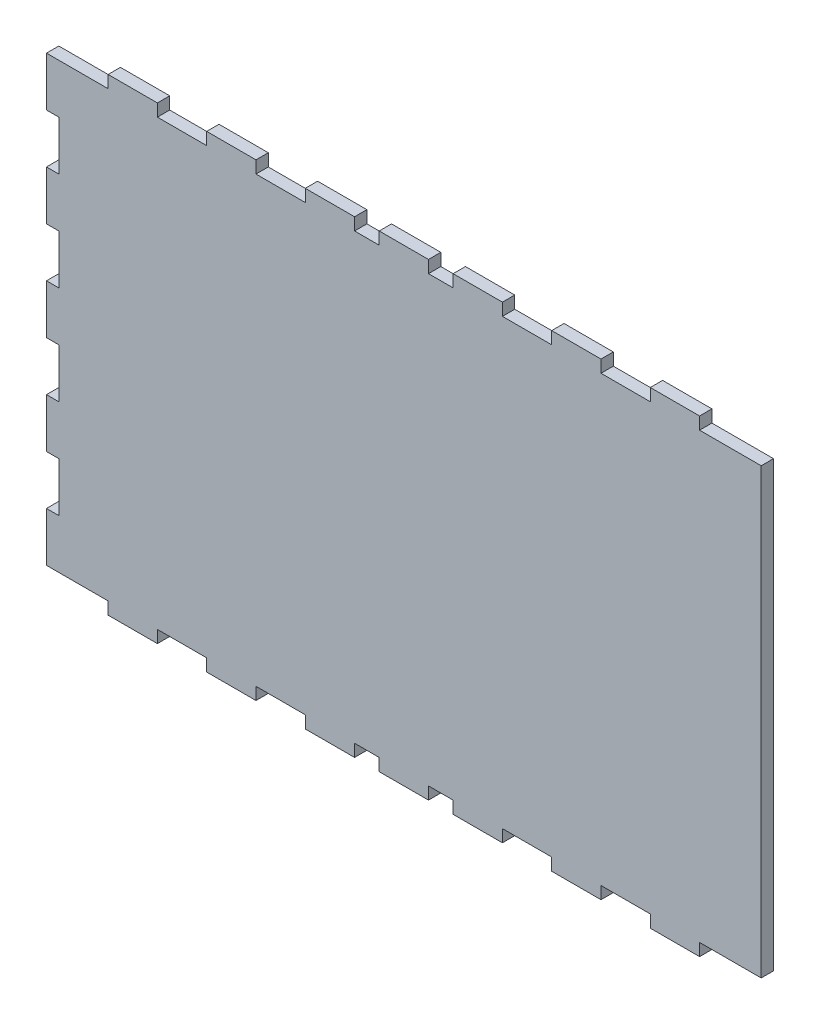
SolidWorks part; units mm, degrees
ref_plane "Front Plane" through (0, 0, 0) normal (0, 0, 1) x (1, 0, 0)
ref_plane "Top Plane" through (0, 0, 0) normal (0, 1, 0) x (1, 0, 0)
ref_plane "Right Plane" through (0, 0, 0) normal (1, 0, 0) x (0, 0, -1)
sketch "Sketch1" plane through (0, 0, 0) normal (0, 0, 1) x (1, 0, 0)
  line L0 (132.5156, 19.2892) -> (164.2656, 19.2892)
  line L1 (164.2656, 19.2892) -> (164.2656, 25.6392)
  line L2 (164.2656, 25.6392) -> (189.6656, 25.6392)
  line L3 (189.6656, 25.6392) -> (189.6656, 19.2892)
  line L4 (189.6656, 19.2892) -> (215.0656, 19.2892)
  line L5 (215.0656, 19.2892) -> (215.0656, 25.6392)
  line L6 (215.0656, 25.6392) -> (240.4656, 25.6392)
  line L7 (240.4656, 25.6392) -> (240.4656, 19.2892)
  line L8 (240.4656, 19.2892) -> (265.8656, 19.2892)
  line L9 (265.8656, 19.2892) -> (265.8656, 25.6392)
  line L10 (265.8656, 25.6392) -> (291.2656, 25.6392)
  line L11 (291.2656, 25.6392) -> (291.2656, 19.2892)
  line L12 (500.8156, 19.2892) -> (469.0656, 19.2892)
  line L13 (469.0656, 19.2892) -> (469.0656, 25.6392)
  line L14 (469.0656, 25.6392) -> (443.6656, 25.6392)
  line L15 (443.6656, 25.6392) -> (443.6656, 19.2892)
  line L16 (443.6656, 19.2892) -> (418.2656, 19.2892)
  line L17 (418.2656, 19.2892) -> (418.2656, 25.6392)
  line L18 (418.2656, 25.6392) -> (392.8656, 25.6392)
  line L19 (392.8656, 25.6392) -> (392.8656, 19.2892)
  line L20 (392.8656, 19.2892) -> (367.4656, 19.2892)
  line L21 (367.4656, 19.2892) -> (367.4656, 25.6392)
  line L22 (367.4656, 25.6392) -> (342.0656, 25.6392)
  line L23 (342.0656, 25.6392) -> (342.0656, 19.2892)
  line L24 (291.2656, 19.2892) -> (303.9656, 19.2892)
  line L25 (303.9656, 19.2892) -> (303.9656, 25.6392)
  line L26 (303.9656, 25.6392) -> (329.3656, 25.6392)
  line L27 (329.3656, 25.6392) -> (329.3656, 19.2892)
  line L28 (329.3656, 19.2892) -> (342.0656, 19.2892)
  line L29 (132.5156, -209.3108) -> (164.2656, -209.3108)
  line L30 (164.2656, -209.3108) -> (164.2656, -215.6608)
  line L31 (164.2656, -215.6608) -> (189.6656, -215.6608)
  line L32 (189.6656, -215.6608) -> (189.6656, -209.3108)
  line L33 (189.6656, -209.3108) -> (215.0656, -209.3108)
  line L34 (215.0656, -209.3108) -> (215.0656, -215.6608)
  line L35 (215.0656, -215.6608) -> (240.4656, -215.6608)
  line L36 (240.4656, -215.6608) -> (240.4656, -209.3108)
  line L37 (240.4656, -209.3108) -> (265.8656, -209.3108)
  line L38 (265.8656, -209.3108) -> (265.8656, -215.6608)
  line L39 (265.8656, -215.6608) -> (291.2656, -215.6608)
  line L40 (291.2656, -215.6608) -> (291.2656, -209.3108)
  line L41 (500.8156, -209.3108) -> (469.0656, -209.3108)
  line L42 (469.0656, -209.3108) -> (469.0656, -215.6608)
  line L43 (469.0656, -215.6608) -> (443.6656, -215.6608)
  line L44 (443.6656, -215.6608) -> (443.6656, -209.3108)
  line L45 (443.6656, -209.3108) -> (418.2656, -209.3108)
  line L46 (418.2656, -209.3108) -> (418.2656, -215.6608)
  line L47 (418.2656, -215.6608) -> (392.8656, -215.6608)
  line L48 (392.8656, -215.6608) -> (392.8656, -209.3108)
  line L49 (392.8656, -209.3108) -> (367.4656, -209.3108)
  line L50 (367.4656, -209.3108) -> (367.4656, -215.6608)
  line L51 (367.4656, -215.6608) -> (342.0656, -215.6608)
  line L52 (342.0656, -215.6608) -> (342.0656, -209.3108)
  line L53 (291.2656, -209.3108) -> (303.9656, -209.3108)
  line L54 (303.9656, -209.3108) -> (303.9656, -215.6608)
  line L55 (303.9656, -215.6608) -> (329.3656, -215.6608)
  line L56 (329.3656, -215.6608) -> (329.3656, -209.3108)
  line L57 (329.3656, -209.3108) -> (342.0656, -209.3108)
  line L58 (500.8156, 19.2892) -> (500.8156, -209.3108)
  line L59 (132.5156, -6.1108) -> (138.8656, -6.1108)
  line L60 (138.8656, -6.1108) -> (138.8656, -31.5108)
  line L61 (138.8656, -31.5108) -> (132.5156, -31.5108)
  line L62 (132.5156, -31.5108) -> (132.5156, -56.9108)
  line L63 (132.5156, -56.9108) -> (138.8656, -56.9108)
  line L64 (138.8656, -56.9108) -> (138.8656, -82.3108)
  line L65 (138.8656, -82.3108) -> (132.5156, -82.3108)
  line L66 (132.5156, -82.3108) -> (132.5156, -107.7108)
  line L67 (132.5156, -107.7108) -> (138.8656, -107.7108)
  line L68 (138.8656, -107.7108) -> (138.8656, -133.1108)
  line L69 (138.8656, -133.1108) -> (132.5156, -133.1108)
  line L70 (132.5156, -133.1108) -> (132.5156, -158.5108)
  line L71 (132.5156, -158.5108) -> (138.8656, -158.5108)
  line L72 (138.8656, -158.5108) -> (138.8656, -183.9108)
  line L73 (138.8656, -183.9108) -> (132.5156, -183.9108)
  line L74 (132.5156, -183.9108) -> (132.5156, -209.3108)
  line L75 (132.5156, -6.1108) -> (132.5156, 19.2892)
extrude "Extrude1" add sketch "Sketch1" along normal blind 6.35
